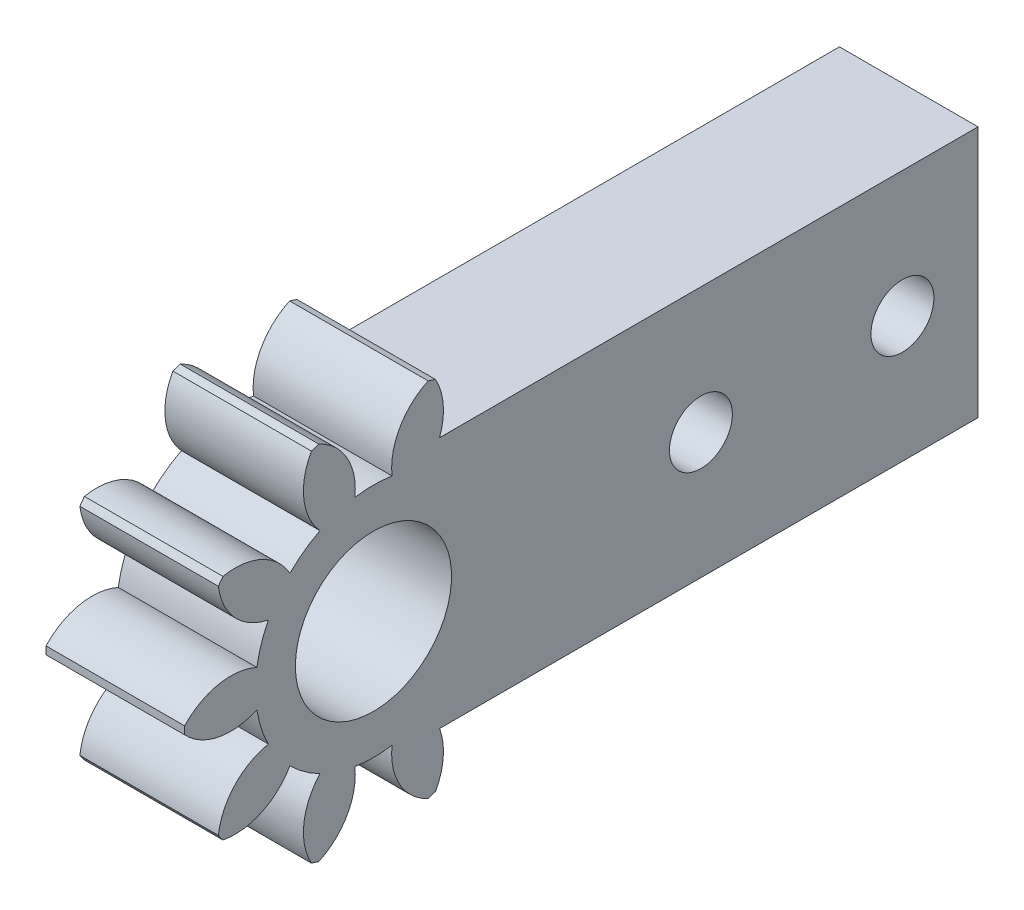
SolidWorks part; units mm, degrees
ref_plane "Plane1" through (0, 0, 0) normal (0, 0, 1) x (1, 0, 0)
ref_plane "Plane2" through (0, 0, 0) normal (0, 1, 0) x (1, 0, 0)
ref_plane "Plane3" through (0, 0, 0) normal (1, 0, 0) x (0, 0, -1)
other "Configuration Table"
sketch "HoldingSke" plane through (0, 0, 0) normal (0, 1, 0) x (1, 0, 0)
  line L0 (0, 0) -> (0.7878, -0.1389)
  line L1 (-15, 0) -> (100, 0) construction
  line L2 (0, 0) -> (-2.1039, 2.3779)
  line L3 (0, 0) -> (-11.863, 4.5341)
  line L4 (0, 0) -> (8.5048, 1.4996)
  line L5 (0, 0) -> (-46.8476, -17.4728)
  line L6 (0, 0) -> (-4.5593, -3.0762)
  line L7 (-2.1039, 2.3779) -> (8.6586, 51.2059)
  line L8 (-76.2, 54.61) -> (-75.2, 54.61)
  line L9 (-71.009, 38.7566) -> (-53.1078, 45.2721)
  line L10 (-76.2, 71.12) -> (104.1128, 71.12)
  line L11 (0, 0) -> (-5.5, 0)
  line L12 (-76.2, 101.6) -> (-76.155, 101.6)
  line L13 (24.9733, 27.94) -> (52.9518, 28.4284)
  line L14 (24.9733, 27.94) -> (24.9743, 27.94)
  line L15 (24.9733, 27.94) -> (100.4006, 29.5858)
  line L16 (-63.627, -1.25) -> (-12.827, -1.25)
  circle A0 centre (0, 0) radius 3
  circle A1 centre (0, 0) radius 4.6865
  circle A2 centre (0, 0) radius 37.5
  circle A3 centre (0, 0) radius 3
  dimension "MHD" = 9.373
  dimension "Hub_dia" = 75
  dimension "Bore" = 6
  dimension "MBD" = 6
  dimension "Num_teeth" = 10
  dimension "Pitch" = 0.8
  dimension "Overall_len" = 50
  dimension "Show_teeth" = 10
  dimension "Thickness" = 5.5
  dimension "OAL" = 50.0001
  dimension "T_dim" = 1
  dimension "Ap" = 20
  dimension "H" = 19.05
  dimension "Pitch_radius" = 180.3128
  dimension "Width" = 5.5
  dimension "Backlash" = 0.045
  dimension "Addendum_fac" = 1
  dimension "Dedendum_fac" = 1.25
  dimension "Clearance_fac" = 0.25
  dimension "Dedendum_add" = 0.001
  dimension "Module" = 1.25
sketch "BasProSke" plane through (0, 0, 0) normal (0, 1, 0) x (1, 0, 0)
  line L0 (-10, 0) -> (60, 0) construction
  line L1 (0, 0) -> (0, 7.5)
  line L2 (0, 0) -> (5.5, 0)
  line L3 (5.5, 0) -> (5.5, 7.5)
  line L4 (5.5, 7.5) -> (0, 7.5)
  dimension "Thickness" = 5.5
  dimension "Diameter" = 15
revolve "Base-Revolve" add sketch "BasProSke" angle 360 about L0
sketch "TooCutSke" plane through (0, 0, 0) normal (1, 0, 0) x (0, 0, -1)
  line L1 (0, 0) -> (0, 107) construction
  line L2 (0, 0) -> (-1.0563, 6.1601) construction
  line L3 (0, 0) -> (-3.8225, 11.7646) construction
  line L4 (-1.0563, 6.1601) -> (-1.9113, 5.8823) construction
  arc A0 (0.7377, 4.6281) -> (-0.7377, 4.6281) centre (0, 0) ccw
  arc A1 (2.2058, 7.1949) -> (-2.2058, 7.1949) centre (0, 0) ccw
  circle A2 centre (0, 0) radius 6.25 construction
  circle A3 centre (0, 0) radius 5.8731 construction
  arc A4 (-0.7377, 4.6281) -> (-2.2058, 7.1949) centre (-3.2217, 4.9106) ccw
  arc A5 (2.2058, 7.1949) -> (0.7377, 4.6281) centre (3.2217, 4.9106) ccw
  dimension "Root_dia" = 9.373
  dimension "Overcut_dia" = 15.0508
  dimension "Pitch_dia" = 12.5
  dimension "Base_dia" = 11.7462
  dimension "Flank_rad" = 2.5
  dimension "Half_ang" = 18
  dimension "Half_CT" = 0.899
extrude "ToothCut" cut sketch "TooCutSke" along normal through all
fillet "Breaks" [suppressed] radius 0.025
fillet "RootFillets" [suppressed] radius 0.3135
pattern_circular "TeethCuts" count 10 every 36 about axis through (-10, 0, 0) along (1, 0, 0) of "ToothCut", "RootFillets", "Breaks"
sketch "HubNeaOneSke" plane through (0, 0, 0) normal (-1, 0, 0) x (0, 0, 1)
  circle A0 centre (0, 0) radius 4.6865
  dimension "Diameter" = 9.373
extrude "HubNearOne" [suppressed] add sketch "HubNeaOneSke" along normal blind 44.5001
sketch "HubNeaBotSke" plane through (0, 0, 0) normal (-1, 0, 0) x (0, 0, 1)
  circle A0 centre (0, 0) radius 4.6865
  dimension "Diameter" = 9.373
extrude "HubNearBoth" [suppressed] add sketch "HubNeaBotSke" along normal blind 22.25
ref_plane "FarPln" through (5.5, 0, 0) normal (1, 0, 0) x (0, 0, -1)
sketch "HubFarSke" plane through (5.5, 0, 0) normal (1, 0, 0) x (0, 0, -1)
  circle A0 centre (0, 0) radius 4.6865
  dimension "Diameter" = 9.373
extrude "HubFar" [suppressed] add sketch "HubFarSke" along normal blind 22.25
sketch "BorSke" plane through (0, 0, 0) normal (1, 0, 0) x (0, 0, -1)
  circle A0 centre (0, 0) radius 3.1
  dimension "Diameter" = 6.2
extrude "Bore" cut sketch "BorSke" along normal mid plane 100.0001
sketch "KeySke" plane through (0, 0, 0) normal (1, 0, 0) x (0, 0, -1)
  line L0 (-1, 0) -> (-1, 4)
  line L1 (-1, 4) -> (1, 4)
  line L2 (1, 4) -> (1, 0)
  line L3 (0, 0) -> (0, 34) construction
  line L4 (-1, 0) -> (1, 0)
  dimension "Offset" = 4
  dimension "Width" = 2
extrude "Keyway" [suppressed] cut sketch "KeySke" along normal mid plane 100.0001
pattern_circular "Keyway2" [suppressed] count 2 every 90 about axis through (-10, 0, 0) along (1, 0, 0)
sketch "ｽｹｯﾁ1" plane through (5.5, 0, 0) normal (1, 0, 0) x (0, 0, -1)
  line L0 (0, 0) -> (13, 0) construction
  line L2 (24, -5) -> (0.7233, -5)
  line L3 (24, -5) -> (24, 5)
  line L4 (24, 5) -> (0.7233, 5)
  line L5 (0.7233, -5) -> (0.7233, 5)
  line L6 (24, -5) -> (0.7233, 5) construction
  line L7 (24, 5) -> (0.7233, -5) construction
  circle A0 centre (13, 0) radius 1.25
  circle A1 centre (0, 0) radius 3.1 construction
  circle A2 centre (21, 0) radius 1.25
  arc A3 (2.1708, 7.179) -> (0.7377, 4.6281) centre (3.2217, 4.9106) ccw construction
  circle A4 centre (0, 0) radius 3.1
  point P5 (12.3616, 0)
  point P13 (26.3509, -1.3952)
  point P14 (27.0242, -3.1905)
  point P15 (0.7217, 4.9106)
  arc M8 (7.4984, 0.1539) -> (4.6295, 0.7286) centre (5.6658, -1.5465) ccw
  arc M9 (4.6295, 0.7286) -> (4.1736, 2.1317) centre (0, 0) ccw
  arc M10 (4.1736, 2.1317) -> (6.1568, 4.2829) centre (3.6747, 4.5814) ccw
  arc M11 (6.1568, 4.2829) -> (5.9759, 4.532) centre (0, 0) ccw
  arc M12 (5.9759, 4.532) -> (3.3171, 3.3106) centre (5.4928, 2.0791) ccw
  arc M13 (3.3171, 3.3106) -> (2.1235, 4.1778) centre (0, 0) ccw
  arc M14 (2.1235, 4.1778) -> (2.4635, 7.0839) centre (0.28, 5.8664) ccw
  arc M40 (2.4635, -7.0839) -> (2.1235, -4.1778) centre (0.28, -5.8664) ccw
  arc M41 (2.1235, -4.1778) -> (3.3171, -3.3106) centre (0, 0) ccw
  arc M42 (3.3171, -3.3106) -> (5.9759, -4.532) centre (5.4928, -2.0791) ccw
  arc M43 (5.9759, -4.532) -> (6.1568, -4.2829) centre (0, 0) ccw
  arc M44 (6.1568, -4.2829) -> (4.1736, -2.1317) centre (3.6747, -4.5814) ccw
  arc M45 (4.1736, -2.1317) -> (4.6295, -0.7286) centre (0, 0) ccw
  arc M46 (4.6295, -0.7286) -> (7.4984, -0.1539) centre (5.6658, 1.5465) ccw
  arc M47 (7.4984, -0.1539) -> (7.4984, 0.1539) centre (0, 0) ccw
  dimension "D1" = 2.5
  dimension "D2" = 13
  dimension "D4" = 8
  dimension "D5" = 3
  dimension "D6" = 10
  dimension "D3" = 2
extrude "ﾎﾞｽ - 押し出し1" add sketch "ｽｹｯﾁ1" against normal up to surface (5.5 mm away) contours L3 L4 L2 A2 A0 M14 M13 M12 M11 M10 M9 M8 M47 M46 M45 M44 M43 M42 M41 M40 up to face at (0, 0, -3.1)
equation "' \"Module@HoldingSke\" = 6.35"
equation "' \"Num_teeth@HoldingSke\" = 12"
equation "' \"Ap@HoldingSke\" =  20"
equation "' \"Ap@HoldingSke\" = 20"
equation "' \"Width@HoldingSke\" = 0.5 * 25.4"
equation "' \"Hub_dia@HoldingSke\"= 1 * 25.4"
equation "' \"Hub_dia@HoldingSke\" = 1 * 25.4"
equation "' \"Overall_len@HoldingSke\" = 1.0 * 25.4"
equation "' \"Bore@HoldingSke\" = 0.75 * 25.4"
equation "' \"T_dim@HoldingSke\" = 0.1 * 25.4"
equation "' \"Width@KeySke\" = 0.25 * 25.4"
equation "' \"Show_teeth@HoldingSke\" = 13"
equation "' \"Backlash@HoldingSke\" = 0.009 * 25.4"
equation "' \"Addendum_fac@HoldingSke\" = 1.0"
equation "' \"Dedendum_fac@HoldingSke\" = 1.25"
equation "' \"Dedendum_add@HoldingSke\" = 0.00005 * 25.4"
equation "' \"Clearance_fac@HoldingSke\" = 0.25"
equation "\"Pitch@HoldingSke\" = 1 / \"Module@HoldingSke\""
equation "\"Overcut_dia@TooCutSke\" = (\"Num_teeth@HoldingSke\" + 2 * \"Addendum_fac@HoldingSke\") / \"Pitch@HoldingSke\" + 0.002 * 25.4"
equation "\"Pitch_dia@TooCutSke\" = \"Num_teeth@HoldingSke\" / \"Pitch@HoldingSke\""
equation "\"Base_dia@TooCutSke\" = \"Num_teeth@HoldingSke\" / \"Pitch@HoldingSke\" * cos((\"Ap@HoldingSke\"  * 3.14159265 / 180))"
equation "\"Root_dia@TooCutSke\" = (\"Num_teeth@HoldingSke\" + 2) / \"Pitch@HoldingSke\" - 2 * (\"Addendum_fac@HoldingSke\" + \"Dedendum_fac@HoldingSke\") / \"Pitch@HoldingSke\" - \"Dedendum_add@HoldingSke\" * 2"
equation "\"Half_ang@TooCutSke\" = 180 / \"Num_teeth@HoldingSke\""
equation "\"Half_CT@TooCutSke\" = \"Num_teeth@HoldingSke\" / \"Pitch@HoldingSke\" * sin((3.14159265 / 2 / \"Num_teeth@HoldingSke\")) / 2 - 7 * \"Backlash@HoldingSke\" / 4"
equation "\"Flank_rad@TooCutSke\" = \"Num_teeth@HoldingSke\" / \"Pitch@HoldingSke\" / 5"
equation "\"Radius@RootFillets\" = \"Clearance_fac@HoldingSke\" / \"Pitch@HoldingSke\" + \"Dedendum_add@HoldingSke\""
equation "\"Break_rad@Breaks\" = 0.02 / \"Pitch@HoldingSke\""
equation "\"Thickness@HoldingSke\" = \"Width@HoldingSke\""
equation "\"OAL@HoldingSke\" = \"Thickness@HoldingSke\""
equation "\"MHD@HoldingSke\" = (\"Num_teeth@HoldingSke\" + 2) / \"Pitch@HoldingSke\" - 2 * (\"Addendum_fac@HoldingSke\" + \"Dedendum_fac@HoldingSke\")  / \"Pitch@HoldingSke\" - \"Dedendum_add@HoldingSke\" * 2"
equation "\"MBD@HoldingSke\" = (\"Num_teeth@HoldingSke\" + 2) / \"Pitch@HoldingSke\" - 2 * (\"Addendum_fac@HoldingSke\" + \"Dedendum_fac@HoldingSke\")  / \"Pitch@HoldingSke\" - \"Dedendum_add@HoldingSke\" * 2 - 0.002 * 25.4"
equation "\"MHD@HoldingSke\" = ((sgn( \"MHD@HoldingSke\" - \"Hub_dia@HoldingSke\" )-1)*( \"MHD@HoldingSke\" - \"Hub_dia@HoldingSke\" ))/-2+ \"Hub_dia@HoldingSke\""
equation "\"MBD@HoldingSke\" = ((sgn( \"MBD@HoldingSke\" - \"Bore@HoldingSke\" )-1)*( \"MBD@HoldingSke\" - \"Bore@HoldingSke\" ))/-2+ \"Bore@HoldingSke\""
equation "\"OAL@HoldingSke\" = ((sgn( \"OAL@HoldingSke\" - \"Overall_len@HoldingSke\" )+1)*( \"OAL@HoldingSke\" - \"Overall_len@HoldingSke\" ))/2 + \"Overall_len@HoldingSke\" + 0.000002 * 25.4"
equation "\"Num_teeth@TeethCuts\" = int( \"Show_teeth@HoldingSke\" ) + 1"
equation "\"Num_teeth@TeethCuts\" = ((sgn( \"Num_teeth@TeethCuts\" - \"Num_teeth@HoldingSke\" )-1)*( \"Num_teeth@TeethCuts\" - \"Num_teeth@HoldingSke\" ))/-2+ \"Num_teeth@HoldingSke\""
equation "\"Num_teeth@TeethCuts\" = ((sgn( \"Num_teeth@TeethCuts\" - 2.0)+1)*( \"Num_teeth@TeethCuts\" - 2.0))/2 +2.0"
equation "\"Angle@TeethCuts\" = 360.0 / \"Num_teeth@HoldingSke\""
equation "\"Diameter@BasProSke\" = (\"Num_teeth@HoldingSke\" + 2 * \"Addendum_fac@HoldingSke\") / \"Pitch@HoldingSke\""
equation "\"Thickness@BasProSke\"  = \"Thickness@HoldingSke\""
equation "' \"Fillet_rad@BasProSke\" =  \"Thickness@HoldingSke\" * 0.05"
equation "' \"Fillet_rad@BasProSke\" = \"Thickness@HoldingSke\" * 0.05"
equation "\"MHD@HoldingSke\" = ((sgn( \"MHD@HoldingSke\" - \"Root_dia@TooCutSke\" )-1)*( \"MHD@HoldingSke\" - \"Root_dia@TooCutSke\" ))/-2+ \"Root_dia@TooCutSke\""
equation "\"Diameter@HubNeaOneSke\" = \"MHD@HoldingSke\""
equation "\"Length@HubNearOne\" = \"OAL@HoldingSke\" - \"Thickness@BasProSke\""
equation "\"Diameter@HubNeaBotSke\" = \"MHD@HoldingSke\""
equation "\"Length@HubNearBoth\" = ( \"OAL@HoldingSke\" - \"Thickness@BasProSke\" ) / 2.0"
equation "\"Thickness@FarPln\" = \"Thickness@BasProSke\""
equation "\"Diameter@HubFarSke\" = \"MHD@HoldingSke\""
equation "\"Length@HubFar\" = ( \"OAL@HoldingSke\" - \"Thickness@BasProSke\" ) / 2.0"
equation "\"D1@Bore\" = \"OAL@HoldingSke\" * 2.0"
equation "\"D1@Keyway\" = \"OAL@HoldingSke\" * 2.0"
equation "\"Offset@KeySke\" = \"T_dim@HoldingSke\" + \"MBD@HoldingSke\" / 2.0"
